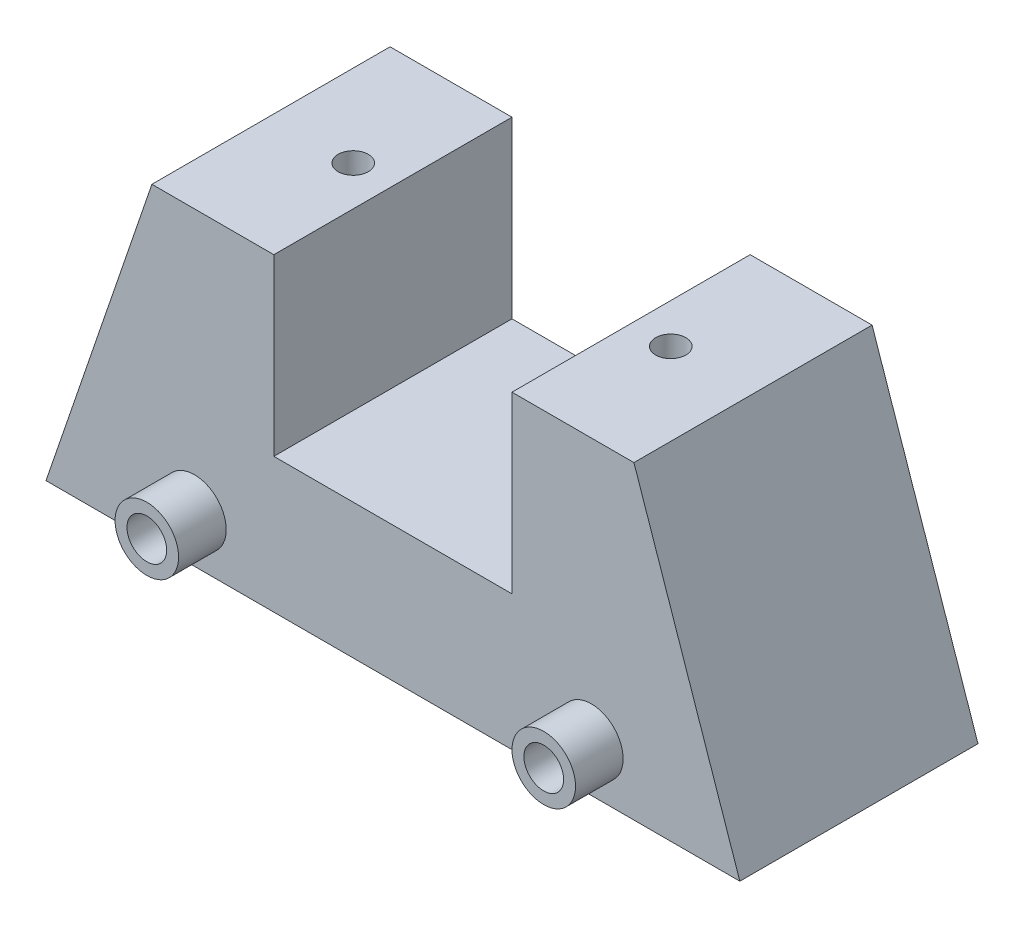
SolidWorks part; units mm, degrees
ref_plane "Front" through (0, 0, 0) normal (0, 0, 1) x (1, 0, 0)
ref_plane "Top" through (0, 0, 0) normal (0, 1, 0) x (1, 0, 0)
ref_plane "Right" through (0, 0, 0) normal (1, 0, 0) x (0, 0, -1)
sketch "Sketch1" plane through (0, 0, 0) normal (0, 0, 1) x (1, 0, 0)
  line L1 (-43.7, 0) -> (43.7, 0)
  line L2 (-43.7, 0) -> (-43.7, 39)
  line L3 (-43.7, 39) -> (43.7, 39)
  line L4 (43.7, 0) -> (43.7, 39)
  point P4 (0, 0)
  dimension "D1" = 87.4
  dimension "D2" = 39
extrude "Boss-Extrude1" add sketch "Sketch1" along normal blind 30
sketch "Sketch2" plane through (0, 0, 30) normal (0, 0, 1) x (1, 0, 0)
  line L8 (-38.6679, 0) -> (38.6679, 0)
  line L9 (38.6679, 0) -> (37.1079, 4.5604)
  line L10 (26.7, 12) -> (-26.7, 12)
  line L11 (-37.1079, 4.5604) -> (-38.6679, 0)
  arc A5 (37.1079, 4.5604) -> (26.7, 12) centre (26.7, 1) ccw
  arc A6 (-26.7, 12) -> (-37.1079, 4.5604) centre (-26.7, 1) ccw
  point P4 (0, 0)
  point P5 (0, 12)
  dimension "D1" = 11
  dimension "D2" = 37.77
  dimension "D3" = 53.4
  dimension "D4" = 12
extrude "Cut-Extrude1" cut sketch "Sketch2" against normal blind 22 from offset 4 offset against normal yes
sketch "Sketch3" plane through (0, 0, 30) normal (0, 0, 1) x (1, 0, 0)
  line L0 (-43.7, 0) -> (-30.3587, 39)
  line L2 (43.7, 39) -> (-43.7, 39) construction
  line L3 (-30.3587, 39) -> (-15, 39) construction
  line L4 (-15, 39) -> (-15, 17)
  line L5 (-15, 17) -> (15, 17)
  line L6 (15, 17) -> (15, 39)
  line L7 (15, 39) -> (30.3587, 39) construction
  line L9 (30.3587, 39) -> (43.7, 0)
  line L10 (-43.7, 0) -> (43.7, 0) construction
  line L11 (-37.1079, 4.5604) -> (-38.6679, 0) construction
  line L12 (26.7, 12) -> (-26.7, 12) construction
  line L13 (-43.7, 0) -> (-43.7, 39)
  line L14 (-43.7, 39) -> (-30.3587, 39)
  line L15 (30.3587, 39) -> (43.7, 39)
  line L16 (43.7, 39) -> (43.7, 0)
  line L17 (15, 39) -> (-15, 39)
  point P13 (0, 17)
  point P18 (0, 0)
  point P24 (0, 0)
  dimension "D1" = 30
  dimension "D3" = 5
extrude "Cut-Extrude2" cut sketch "Sketch3" against normal through all contours L0 L14 L13
sketch "Sketch4" plane through (0, 39, 0) normal (0, 1, 0) x (1, 0, 0)
  line L0 (20, -15) -> (-20, -15) construction
  line L1 (-15, 0) -> (-15, -30) construction
  circle A0 centre (-20, -15) radius 1.9
  circle A1 centre (20, -15) radius 1.9
  point P0 (0, -15)
  point P4 (0, 0)
  point P9 (-15, -15)
  dimension "D2" = 3.8
  dimension "D1" = 40
extrude "Cut-Extrude3" cut sketch "Sketch4" against normal blind 15
sketch "Sketch5" plane through (0, 0, 30) normal (0, 0, 1) x (1, 0, 0)
  line L0 (-25, 6) -> (25, 6) construction
  line L1 (-43.7, 0) -> (43.7, 0) construction
  circle A0 centre (25, 6) radius 4
  circle A1 centre (-25, 6) radius 4
  point P4 (0, 6)
  point P7 (0, 0)
  dimension "D2" = 8
  dimension "D1" = 50
  dimension "D3" = 6
extrude "Boss-Extrude2" add sketch "Sketch5" along normal blind 6
sketch "Sketch6" plane through (0, 0, 36) normal (0, 0, 1) x (1, 0, 0)
  circle A0 centre (25, 6) radius 2.5
  circle A1 centre (-25, 6) radius 2.5
  dimension "D1" = 5
extrude "Cut-Extrude4" cut sketch "Sketch6" against normal up to surface (10 mm away) up to face at (0, 6.0763, 26)
